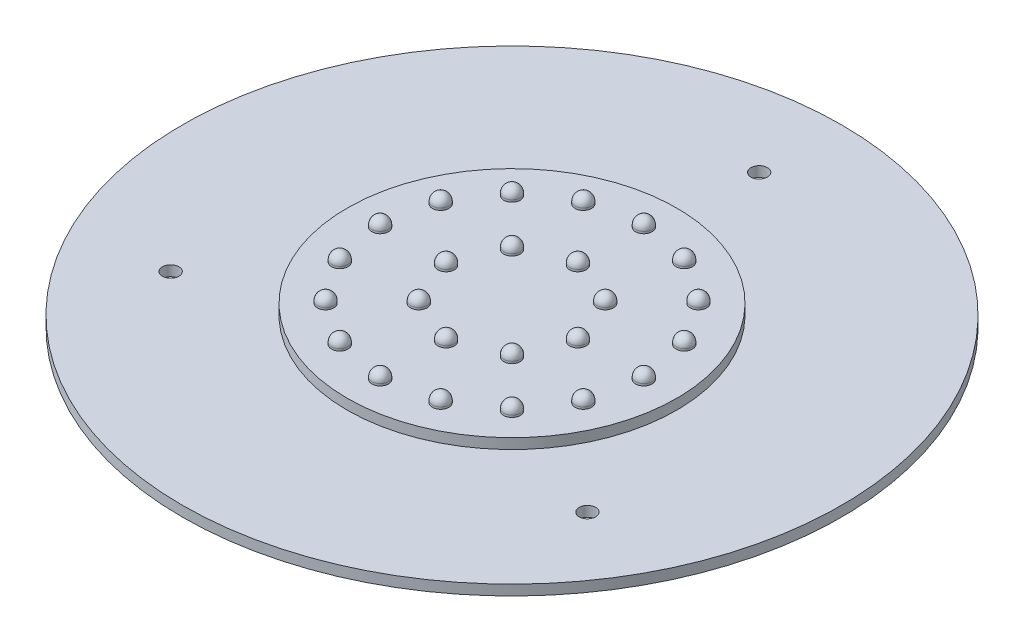
SolidWorks part; units mm, degrees
ref_plane "前视基准面" through (0, 0, 0) normal (0, 0, 1) x (1, 0, 0)
ref_plane "上视基准面" through (0, 0, 0) normal (0, 1, 0) x (1, 0, 0)
ref_plane "右视基准面" through (0, 0, 0) normal (1, 0, 0) x (0, 0, -1)
sketch "草图1" plane through (0, 0, 0) normal (0, 1, 0) x (1, 0, 0)
  circle A0 centre (0, 0) radius 80
extrude "凸台-拉伸1" add sketch "草图1" along normal blind 5
sketch "草图2" plane through (0, 0, 0) normal (0, 1, 0) x (1, 0, 0)
  circle A0 centre (0, 0) radius 160
extrude "凸台-拉伸2" add sketch "草图2" against normal blind 5
sketch "草图3" plane through (0, 0, 0) normal (0, 1, 0) x (1, 0, 0)
  line L0 (0, 169.3074) -> (0, 0) construction
  line L1 (0, 0) -> (0, -172.1345) construction
  line L4 (134.8793, -86.0672) -> (0, 0) construction
  line L5 (0, 0) -> (-134.8793, -86.0672) construction
  circle A0 centre (0, 0) radius 160 construction
  circle A1 centre (0, 0) radius 120
hole_wizard "大小mm 暗销孔1" positions "3D草图2" profile "草图4" hole size "Ø8.0" standard "ISO"
sketch3d "3D草图2"
  line L0 (0, 0, -169.3074) -> (0, 0, 0) construction
  line L1 (0, 0, 0) -> (-134.8793, 0, 86.0672) construction
  line L2 (134.8793, 0, 86.0672) -> (0, 0, 0) construction
  circle A0 centre (0, 0, 0) radius 120 construction
  point P0 (0, 0, -120)
  point P4 (0, 120, 0)
  point P7 (-101.1595, 0, 64.5504)
  point P11 (101.1595, 0, 64.5504)
sketch "草图4" plane through (0, 0, -120) normal (1, 0, 0) x (0, 0, 1)
  line L0 (0, 0) -> (0, 12.4034)
  line L1 (0, 12.4034) -> (4, 10)
  line L2 (4, 10) -> (4, 0)
  line L5 (4, 0) -> (0, 0)
  line L10 (0, 12.4034) -> (-4, 10) construction
  line L11 (0, -6.35) -> (0, 107.95) construction
  dimension "孔直径" = 8
  dimension "孔深度" = 10
  dimension "导头角度" = 118
sketch "草图5" plane through (0, 5, 0) normal (0, 1, 0) x (1, 0, 0)
  circle A0 centre (0, 0) radius 64
sketch "草图6" plane through (0, 5, 0) normal (0, 1, 0) x (1, 0, 0)
  circle A0 centre (0, 64) radius 4
  circle A1 centre (0, 0) radius 64 construction
  circle A2 centre (24.4917, 59.1283) radius 4
  circle A3 centre (45.2548, 45.2548) radius 4
  circle A4 centre (59.1283, 24.4917) radius 4
  circle A5 centre (64, 0) radius 4
  circle A6 centre (59.1283, -24.4917) radius 4
  circle A7 centre (45.2548, -45.2548) radius 4
  circle A8 centre (24.4917, -59.1283) radius 4
  circle A9 centre (0, -64) radius 4
  circle A10 centre (-24.4917, -59.1283) radius 4
  circle A11 centre (-45.2548, -45.2548) radius 4
  circle A12 centre (-59.1283, -24.4917) radius 4
  circle A13 centre (-64, 0) radius 4
  circle A14 centre (-59.1283, 24.4917) radius 4
  circle A15 centre (-45.2548, 45.2548) radius 4
  circle A16 centre (-24.4917, 59.1283) radius 4
  point P36 (0, 0)
  dimension "D1" = 16
extrude "凸台-拉伸3" add sketch "草图6" along normal blind 5
fillet "圆角1" radius 4 16 edges at (59.1283, 10, -20.4917) (45.2548, 10, -41.2548) (64, 10, 4) (59.1283, 10, 28.4917) (45.2548, 10, 49.2548) (24.4917, 10, 63.1283) (0, 10, 68) (-24.4917, 10, 63.1283) (-45.2548, 10, 49.2548) (-59.1283, 10, 28.4917) (-64, 10, 4) (-59.1283, 10, -20.4917) (-45.2548, 10, -41.2548) (-24.4917, 10, -55.1283) (0, 10, -60) (24.4917, 10, -55.1283)
sketch "草图7" plane through (0, 5, 0) normal (0, 1, 0) x (1, 0, 0)
  circle A0 centre (0, 0) radius 32
sketch "草图8" plane through (0, 5, 0) normal (0, 1, 0) x (1, 0, 0)
  circle A0 centre (0, 32) radius 4
  circle A1 centre (0, 0) radius 32 construction
  circle A2 centre (22.6274, 22.6274) radius 4
  circle A3 centre (32, 0) radius 4
  circle A4 centre (22.6274, -22.6274) radius 4
  circle A5 centre (0, -32) radius 4
  circle A6 centre (-22.6274, -22.6274) radius 4
  circle A7 centre (-32, 0) radius 4
  circle A8 centre (-22.6274, 22.6274) radius 4
  point P21 (0, 0)
  dimension "D1" = 8
extrude "凸台-拉伸4" add sketch "草图8" along normal blind 5
fillet "圆角2" radius 4 8 edges at (-22.6274, 10, -18.6274) (-32, 10, 4) (-22.6274, 10, 26.6274) (0, 10, 36) (22.6274, 10, 26.6274) (32, 10, 4) (22.6274, 10, -18.6274) (0, 10, -28)
